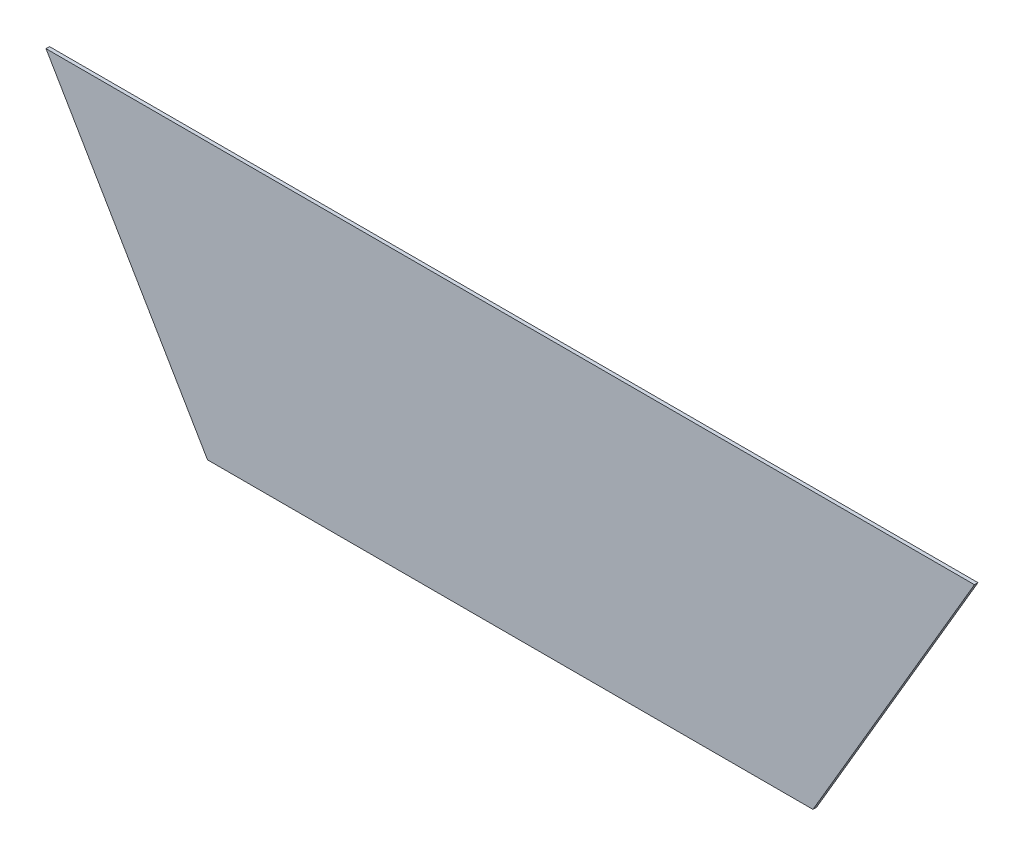
SolidWorks part; units mm, degrees
ref_plane "Front Plane" through (0, 0, 0) normal (1, 0, 0) x (0, 1, 0)
ref_plane "Top Plane" through (0, 0, 0) normal (0, 0, 1) x (0, 1, 0)
ref_plane "Right Plane" through (0, 0, 0) normal (0, 1, 0) x (-1, 0, 0)
sketch "Sketch1" plane through (0, 0, 11.943) normal (0, 0, -1) x (-1, 0, 0)
  line L13 (-171.5, 0) -> (171.5, 0)
  line L15 (171.5, 0) -> (263, 156)
  line L16 (263, 156) -> (-263, 156)
  line L17 (-263, 156) -> (-171.5, 0)
  point P3 (0, 0)
  dimension "D1" = 526
  dimension "D2" = 343
  dimension "D3" = 156
extrude "Boss-Extrude1" add sketch "Sketch1" along normal blind 2
sketch "Sketch2" plane through (0, 0, 11.943) normal (0, 0, 1) x (1, 0, 0)
  circle A0 centre (111.0321, 95) radius 2.5
  circle A1 centre (111.0321, 80) radius 2.5
  circle A2 centre (-113.9679, 95) radius 2.5
  circle A3 centre (-113.9679, 80) radius 2.5
